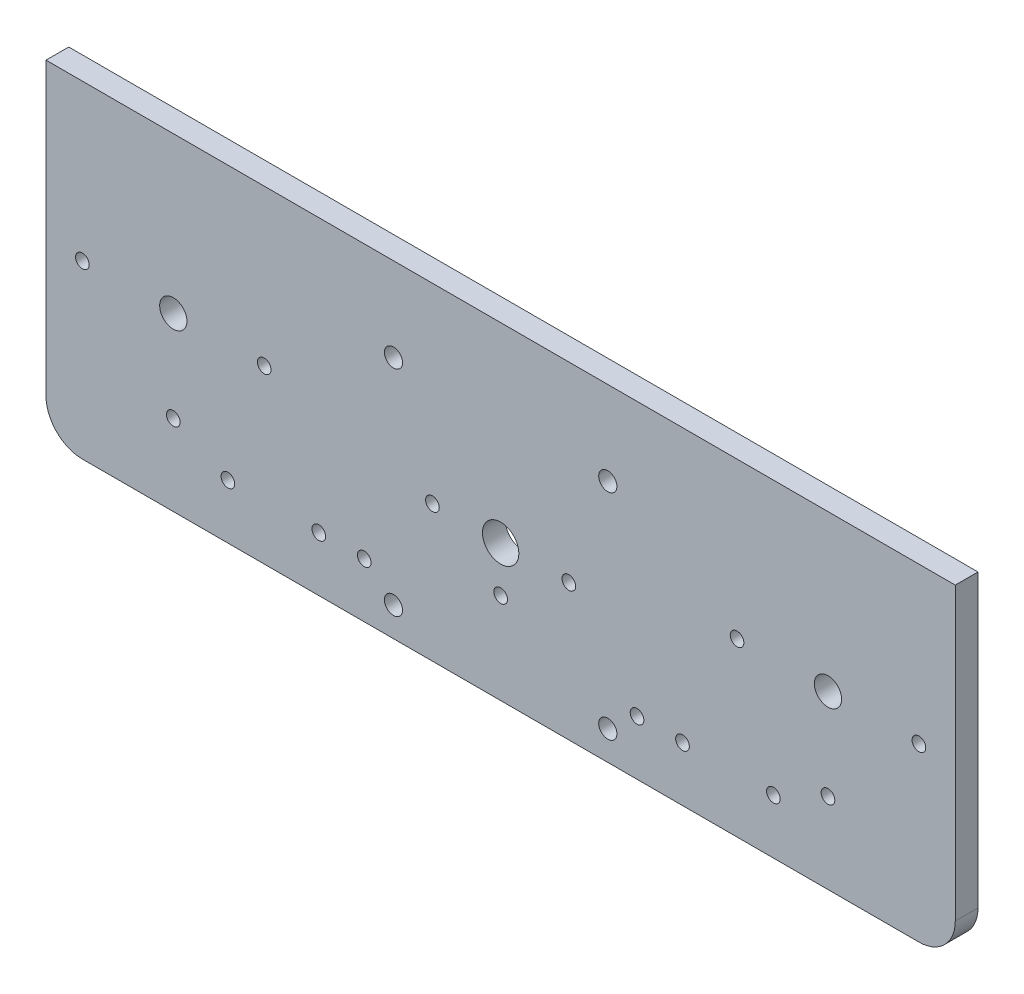
SolidWorks part; units mm, degrees
ref_plane "Alzado" through (0, 0, 0) normal (0, 0, 1) x (1, 0, 0)
ref_plane "Planta" through (0, 0, 0) normal (0, 1, 0) x (1, 0, 0)
ref_plane "Vista lateral" through (0, 0, 0) normal (1, 0, 0) x (0, 0, -1)
sketch "Croquis1" plane through (0, 0, 0) normal (0, 0, 1) x (1, 0, 0)
  line L0 (2.0685, -0.3273) -> (102.0685, -0.3273) construction
  line L1 (2.0685, -0.3273) -> (2.0685, -27.3273) construction
  line L2 (74.0685, -0.3273) -> (74.0685, -19.5773) construction
  line L3 (102.0685, -0.3273) -> (102.0685, -49.3273)
  line L4 (94.0685, -57.3273) -> (-89.9315, -57.3273)
  line L5 (2.0685, -57.3273) -> (2.0685, -27.3273) construction
  line L6 (2.0685, -0.3273) -> (2.0685, 14.6727) construction
  line L7 (-97.9315, 14.6727) -> (102.0685, 14.6727)
  line L8 (102.0685, 14.6727) -> (102.0685, -0.3273)
  line L9 (-97.9315, 14.6727) -> (-97.9315, -0.3273)
  line L10 (-97.9315, -0.3273) -> (-97.9315, -49.3273)
  line L11 (2.0685, -27.3273) -> (102.0685, -27.3273) construction
  line L12 (-21.5015, -50.8973) -> (25.6385, -50.8973) construction
  line L13 (-21.5015, -50.8973) -> (-21.5015, -3.7573) construction
  line L14 (-21.5015, -3.7573) -> (25.6385, -3.7573) construction
  line L15 (25.6385, -50.8973) -> (25.6385, -3.7573) construction
  line L16 (-21.5015, -50.8973) -> (25.6385, -3.7573) construction
  line L17 (-21.5015, -3.7573) -> (25.6385, -50.8973) construction
  circle A0 centre (2.0685, -27.3273) radius 4
  circle A1 centre (74.0685, -19.5773) radius 3
  circle A2 centre (-69.9315, -19.5773) radius 3
  circle A3 centre (74.0685, -39.5773) radius 1.5
  circle A4 centre (54.0685, -19.5773) radius 1.5
  circle A5 centre (94.0685, -19.5773) radius 1.5
  circle A6 centre (-69.9315, -19.5773) radius 3
  circle A7 centre (-69.9315, -39.5773) radius 1.5
  circle A8 centre (-89.9315, -19.5773) radius 1.5
  circle A9 centre (-49.9315, -19.5773) radius 1.5
  arc A10 (102.0685, -49.3273) -> (94.0685, -57.3273) centre (94.0685, -49.3273) cw
  arc A11 (-97.9315, -49.3273) -> (-89.9315, -57.3273) centre (-89.9315, -49.3273) ccw
  circle A12 centre (42.0685, -45.3273) radius 1.5
  circle A13 centre (62.0685, -45.3273) radius 1.5
  circle A14 centre (-57.9315, -45.3273) radius 1.5
  circle A15 centre (-37.9315, -45.3273) radius 1.5
  circle A16 centre (-12.9315, -27.3273) radius 1.5
  circle A17 centre (17.0685, -27.3273) radius 1.5
  circle A18 centre (2.0685, -37.3273) radius 1.5
  circle A19 centre (-21.5015, -3.7573) radius 2
  circle A20 centre (25.6385, -3.7573) radius 2
  circle A21 centre (25.6385, -50.8973) radius 2
  circle A22 centre (-21.5015, -50.8973) radius 2
  circle A23 centre (32.0685, -45.3273) radius 1.5
  circle A24 centre (-27.9315, -45.3273) radius 1.5
  dimension "D4" = 8
  dimension "D5" = 6
  dimension "D10" = 3
  dimension "D11" = 3
  dimension "D13" = 8
  dimension "D14" = 3
  dimension "D15" = 3
  dimension "D19" = 3
  dimension "D21" = 3
  dimension "D24" = 4
  dimension "D25" = 3
  dimension "D1" = 19.25
  dimension "D2" = 27
  dimension "D3" = 72
  dimension "D6" = 100
  dimension "D7" = 47.14
  dimension "D8" = 20
  dimension "D9" = 20
  dimension "D12" = 15
  dimension "D16" = 20
  dimension "D17" = 40
  dimension "D18" = 12
  dimension "D20" = 15
  dimension "D22" = 10
  dimension "D23" = 47.14
  dimension "D26" = 30
extrude "Saliente-Extruir1" add sketch "Croquis1" along normal blind 5 contours L10 A11 L4 A10 L3 L8 L7 L9 A20 A19 A18 A15 A7 A2 A1 A0 A3 A4 A5 A8 A9 A12 A13 A14 A16 A17 A21 A22
